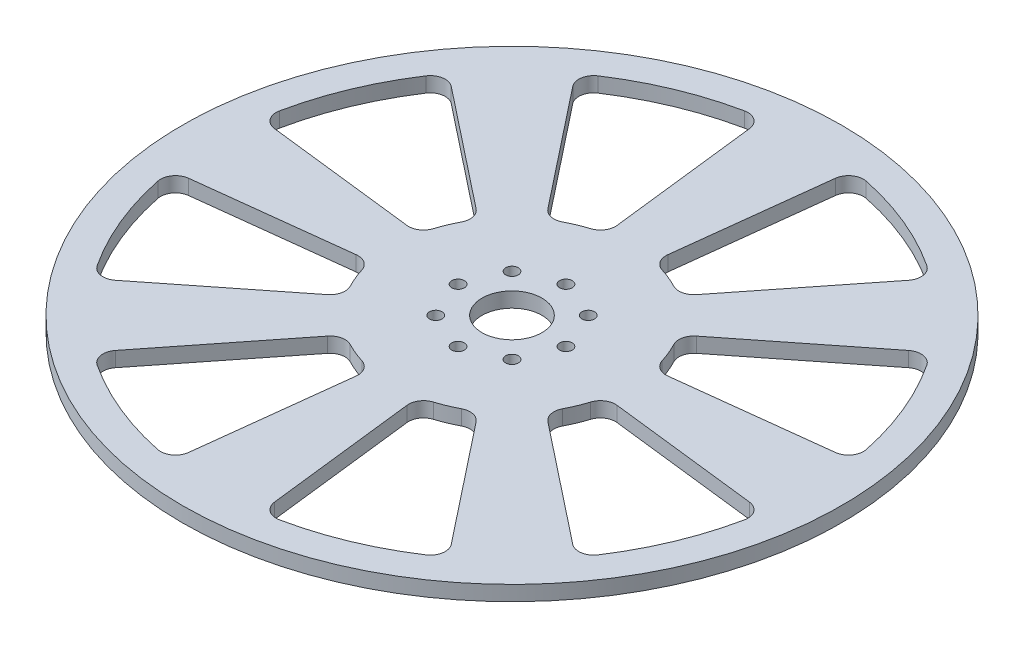
SolidWorks part; units mm, degrees
ref_plane "Спереди" through (0, 0, 0) normal (0, 0, 1) x (1, 0, 0)
ref_plane "Сверху" through (0, 0, 0) normal (0, 1, 0) x (1, 0, 0)
ref_plane "Справа" through (0, 0, 0) normal (1, 0, 0) x (0, 0, -1)
sketch "Эскиз1" plane through (0, 0, 0) normal (0, 1, 0) x (1, 0, 0)
  line L40 (-14.9578, -98.875) -> (-7.9599, -39.2)
  line L41 (14.9578, -98.875) -> (7.9599, -39.2)
  line L42 (80.4919, -59.3385) -> (33.3471, -22.0901)
  line L43 (22.0901, -33.3471) -> (59.3385, -80.4919)
  line L44 (98.875, -14.9578) -> (39.2, -7.9599)
  line L45 (39.2, 7.9599) -> (98.875, 14.9578)
  line L46 (33.3471, 22.0901) -> (80.4919, 59.3385)
  line L47 (22.0901, 33.3471) -> (59.3385, 80.4919)
  line L48 (7.9599, 39.2) -> (14.9578, 98.875)
  line L49 (-7.9599, 39.2) -> (-14.9578, 98.875)
  line L50 (-22.0901, 33.3471) -> (-59.3385, 80.4919)
  line L51 (-33.3471, 22.0901) -> (-80.4919, 59.3385)
  line L52 (-39.2, 7.9599) -> (-98.875, 14.9578)
  line L53 (-98.875, -14.9578) -> (-39.2, -7.9599)
  line L54 (-33.3471, -22.0901) -> (-80.4919, -59.3385)
  line L55 (-59.3385, -80.4919) -> (-22.0901, -33.3471)
  circle A0 centre (0, 0) radius 40
  circle A1 centre (0, 0) radius 10
  circle A2 centre (0, 0) radius 110
  circle A3 centre (0, 0) radius 100
  circle A13 centre (0, 0) radius 25
  circle A15 centre (0, 18) radius 2.1
  circle A16 centre (12.7279, -12.7279) radius 2.1
  circle A17 centre (-18, 0) radius 2.1
  circle A18 centre (0, -18) radius 2.1
  circle A19 centre (-12.7279, -12.7279) radius 2.1
  circle A20 centre (18, 0) radius 2.1
  circle A21 centre (12.7279, 12.7279) radius 2.1
  circle A22 centre (-12.7279, 12.7279) radius 2.1
extrude "Бобышка-Вытянуть3" add sketch "Эскиз1" along normal blind 5 contours A2 A3 | L52 A3 L53 A0 | L50 A3 L51 A0 | L48 A3 L49 A0 | L46 A3 L47 A0 | L44 A3 L45 A0 | L43 A3 L42 A0 | L40 A3 L41 A0 | L54 A3 L55 A0 | A0 A13 | A13 A22 A21 A20 A19 A18 A17 A16 A15 A1
fillet "Скругление2" radius 5 32 edges at (-39.2, 2.5, 7.9599) (-33.3471, 2.5, 22.0901) (-80.4919, 2.5, 59.3385) (-98.875, 2.5, 14.9578) (-14.9578, 2.5, 98.875) (-7.9599, 2.5, 39.2) (-22.0901, 2.5, 33.3471) (-59.3385, 2.5, 80.4919) (7.9599, 2.5, 39.2) (14.9578, 2.5, 98.875) (59.3385, 2.5, 80.4919) (22.0901, 2.5, 33.3471) (33.3471, 2.5, 22.0901) (80.4919, 2.5, 59.3385) (98.875, 2.5, 14.9578) (39.2, 2.5, 7.9599) (98.875, 2.5, -14.9578) (80.4919, 2.5, -59.3385) (33.3471, 2.5, -22.0901) (39.2, 2.5, -7.9599) (59.3385, 2.5, -80.4919) (14.9578, 2.5, -98.875) (7.9599, 2.5, -39.2) (22.0901, 2.5, -33.3471) (-7.9599, 2.5, -39.2) (-22.0901, 2.5, -33.3471) (-59.3385, 2.5, -80.4919) (-14.9578, 2.5, -98.875) (-98.875, 2.5, -14.9578) (-39.2, 2.5, -7.9599) (-33.3471, 2.5, -22.0901) (-80.4919, 2.5, -59.3385)
sketch3d "Трехмерный эскиз1"
  point P0 (9.607, 5, 24.5006)
sketch3d "Трехмерный эскиз2"
  point P0 (-10.5704, 5, -24.5175)
